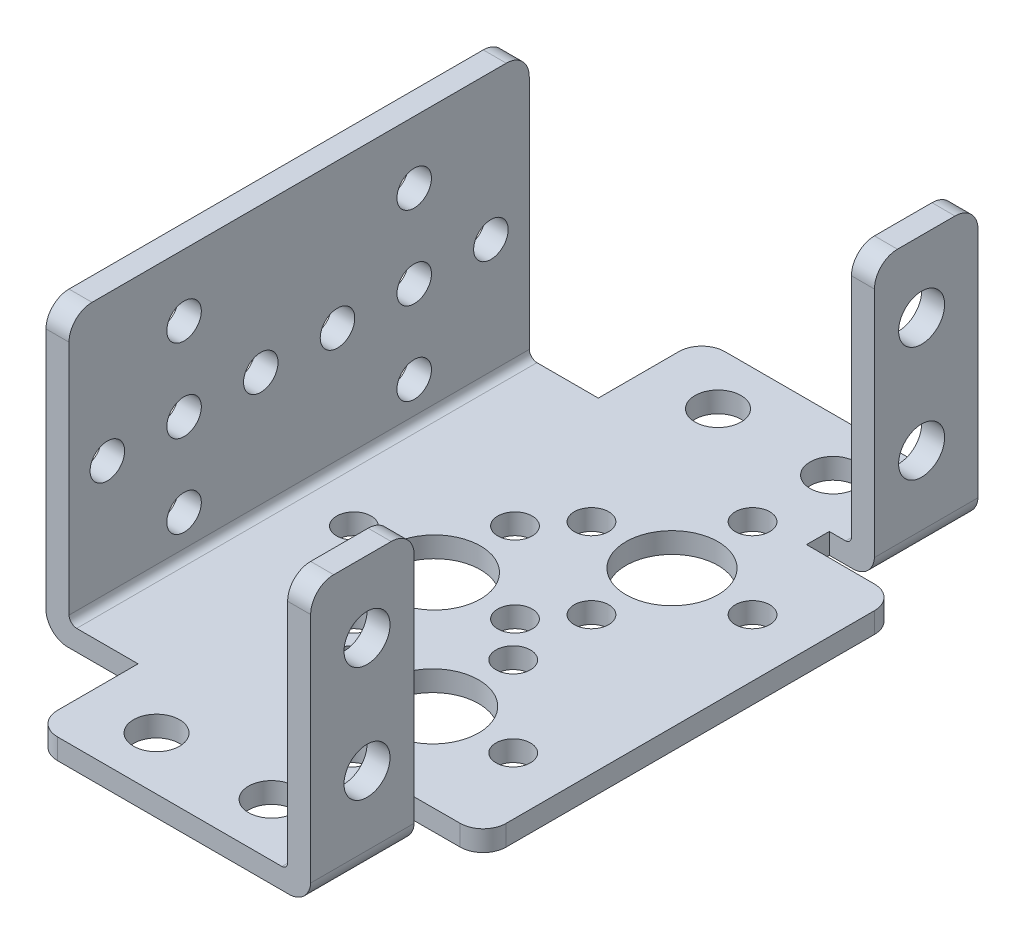
SolidWorks part; units mm, degrees
material "1060 Alloy"
ref_plane "Front Plane" through (0, 0, 0) normal (0, 0, 1) x (1, 0, 0)
ref_plane "Top Plane" through (0, 0, 0) normal (0, 1, 0) x (1, 0, 0)
ref_plane "Right Plane" through (0, 0, 0) normal (1, 0, 0) x (0, 0, -1)
sketch "Sketch2" plane through (0, 0, 0) normal (0, 0, 1) x (1, 0, 0)
  line L0 (1.7922, 0) -> (36, 0)
  line L1 (0, 1.7922) -> (0, 25)
  line L2 (0, 25) -> (2, 25)
  line L3 (2, 25) -> (2, 2.4579)
  line L4 (2.6657, 1.7922) -> (36, 1.7922)
  line L5 (36, 1.7922) -> (36, 0)
  arc A0 (2, 0) -> (0, 1.7922) centre (1.8961, 1.8961) cw
  arc A1 (2, 2.4579) -> (2.6657, 1.7922) centre (2.7075, 2.4997) ccw
extrude "Boss-Extrude1" add sketch "Sketch2" along normal blind 40 contours A1 L3 L2 L1 A0 L0 L5 L4
fillet "Fillet1" radius 2 4 edges at (36, 0.8961, 40) (36, 0.8961, 0) (1, 25, 0) (1, 25, 40)
sketch "Sketch3" plane through (0, 0, 0) normal (0, 0, -1) x (-1, 0, 0)
  line L1 (-2.6657, 1.7922) -> (-34, 1.7922) construction
  line L2 (-8, 1.7922) -> (-8, 0)
  line L3 (-1.7922, 0) -> (-34, 0) construction
  line L4 (-8, 0) -> (-30.2078, 0)
  line L5 (-32, 1.7922) -> (-32, 24)
  line L6 (-32, 24) -> (-30, 24)
  line L7 (-30, 24) -> (-30, 2.2866)
  line L8 (-29.5056, 1.7922) -> (-8, 1.7922)
  arc A0 (-30, 0) -> (-32, 1.7922) centre (-30.1039, 1.8961) cw
  arc A1 (-29.5056, 1.7922) -> (-30, 2.2866) centre (-29.4772, 2.315) cw
  line M8 (-2.6657, 1.7922) -> (-34, 1.7922)
  line M10 (-34, 0) -> (-1.7922, 0)
extrude "Boss-Extrude2" add sketch "Sketch3" along normal blind 9 contours A1 L7 L6 L5 M8 | A0 L4 L2 M10 M8
fillet "Fillet2" radius 2 3 edges at (8, 0.8961, -9) (31, 24, 0) (31, 24, -9)
sketch "Sketch4" plane through (0, 1.7922, 0) normal (0, 1, 0) x (1, 0, 0)
  line L1 (28.0756, 0) -> (28.0756, -1.9781)
  line L2 (28.0756, -1.9781) -> (36, -2)
  line L3 (34, 0) -> (28.0756, 0)
  arc A0 (36, -2) -> (34, 0) centre (34.0055, -1.9945) ccw
extrude "Cut-Extrude1" cut sketch "Sketch4" against normal blind 9
fillet "Fillet3" radius 2 1 edges
ref_plane "Plane1" through (0, 0, 20) normal (0, 0, -1) x (-1, 0, 0)
mirror "Mirror3" about plane through (0, 0, 20) normal (0, 0, -1) of "Fillet2", "Boss-Extrude2", "Cut-Extrude1", "Fillet3"
sketch "Sketch5" plane through (0, 0, 0) normal (-1, 0, 0) x (0, 0, 1)
  line L0 (39.4142, 24.4142) -> (39.4142, 12.4142) construction
  line L1 (40, 12.3961) -> (36.6667, 12.3961) construction
  line L2 (40, 1.7922) -> (40, 23) construction
  line L3 (30, 12.3961) -> (30, 19.5961) construction
  line L4 (30, 12.3961) -> (30, 5.1961) construction
  line L5 (10, 12.3961) -> (10, 19.5961) construction
  line L6 (10, 12.3961) -> (10, 5.1961) construction
  line L7 (0, 1.7922) -> (0, 23) construction
  arc A0 (40, 23) -> (38, 25) centre (38, 23) ccw construction
  circle A1 centre (36.6667, 12.3961) radius 1.5
  circle A2 centre (30, 12.3961) radius 1.5
  circle A3 centre (23.3333, 12.3961) radius 1.5
  circle A4 centre (16.6667, 12.3961) radius 1.5
  circle A5 centre (10, 12.3961) radius 1.5
  circle A6 centre (3.3333, 12.3961) radius 1.5
  circle A7 centre (30, 19.5961) radius 1.5
  circle A8 centre (30, 5.1961) radius 1.5
  circle A9 centre (10, 19.5961) radius 1.5
  circle A10 centre (10, 5.1961) radius 1.5
  point P28 (0, 0)
  point P29 (0, 0)
  point P32 (0, 0)
  point P34 (-18.5196, 24.364)
  dimension "D1" = 6
  dimension "D2" = 20
  dimension "D3" = 10
extrude "Cut-Extrude2" cut sketch "Sketch5" against normal blind 9 contours A2 | A1 | A3 | A4 | A5 | A6 | A7 | A9 | A10 | A8
sketch "Sketch7" plane through (0, 1.7922, 0) normal (0, 1, 0) x (1, 0, 0)
  line L0 (29.5056, -49) -> (29.5056, -40) construction
  line L2 (30.2078, -49) -> (10, -49) construction
  circle A0 centre (24.0056, -44.4) radius 2
  circle A1 centre (14.0056, -44.4) radius 2
  point P4 (0, 0)
  point P6 (0, 0)
  dimension "D1" = 4.6
  dimension "D3" = 4
  dimension "D5" = 4
  dimension "D2" = 4.6
  dimension "D4" = 10
  dimension "D6" = 5.5
extrude "Cut-Extrude3" cut sketch "Sketch7" against normal blind 9 contours A0 | A1
mirror "Mirror4" about plane through (0, 0, 20) normal (0, 0, -1) of "Cut-Extrude3"
sketch "Sketch8" plane through (30, 0, 0) normal (-1, 0, 0) x (0, 0, 1)
  line L2 (49, 1.7922) -> (49, 22) construction
  line L4 (49, 1.7922) -> (40, 1.7922) construction
  circle A0 centre (44.1, 17.7922) radius 2
  circle A1 centre (44.1, 7.7922) radius 2
  point P4 (0, 0)
  point P6 (44.5165, 12.8405)
  point P8 (0, 0)
  point P11 (43.019, 24)
  point P12 (91.5015, 43.3145)
  point P13 (0, 0)
  point P14 (0, 0)
  dimension "D1" = 4
  dimension "D2" = 4
  dimension "D3" = 10
  dimension "D4" = 4.9
  dimension "D5" = 6
extrude "Cut-Extrude4" cut sketch "Sketch8" against normal blind 9 contours A0 | A1
mirror "Mirror5" about plane through (0, 0, 20) normal (0, 0, -1) of "Cut-Extrude4"
sketch "Sketch9" plane through (0, 1.7922, 0) normal (0, 1, 0) x (1, 0, 0)
  line L0 (24.0056, 4.4) -> (24.0056, -9.6) construction
  circle A0 centre (24.0056, -9.6) radius 4
  circle A1 centre (24.0056, -2.6) radius 1.5
  circle A2 centre (31.0056, -9.6) radius 1.5
  circle A3 centre (24.0056, -16.6) radius 1.5
  circle A4 centre (17.0056, -9.6) radius 1.5
  point P2 (0, 0)
  point P3 (0, 0)
  point P6 (0, 0)
  point P19 (24.0056, -9.6)
  dimension "D1" = 4
  dimension "D2" = 8
  dimension "D3" = 3
  dimension "D4" = 7
extrude "Cut-Extrude5" cut sketch "Sketch9" against normal blind 9 contours A0 | A2 | A4 | A3 | A1
mirror "Mirror6" about plane through (0, 0, 20) normal (0, 0, -1) of "Cut-Extrude5"
sketch "Sketch10" plane through (0, 1.7922, 0) normal (0, 1, 0) x (1, 0, 0)
  line L0 (14.0056, 4.4) -> (14.0056, -20.2455) construction
  circle A0 centre (14.0056, -20.2455) radius 4
  circle A1 centre (14.0056, -13.2455) radius 1.5
  circle A2 centre (21.0056, -20.2455) radius 1.5
  circle A3 centre (14.0056, -20.2455) radius 4
  circle A4 centre (14.0056, -27.2455) radius 1.5
  circle A5 centre (14.0056, -20.2455) radius 4
  circle A6 centre (7.0056, -20.2455) radius 1.5
  circle A7 centre (14.0056, -20.2455) radius 4
  point P6 (0, 0)
  point P7 (0, 0)
  point P18 (14.0056, -20.2455)
  dimension "D1" = 4
  dimension "D2" = 3
  dimension "D3" = 8
  dimension "D4" = 7
extrude "Cut-Extrude6" cut sketch "Sketch10" against normal blind 9 contours A1 L0 | L0 A1 | A6 | A2 | A4 | A5
